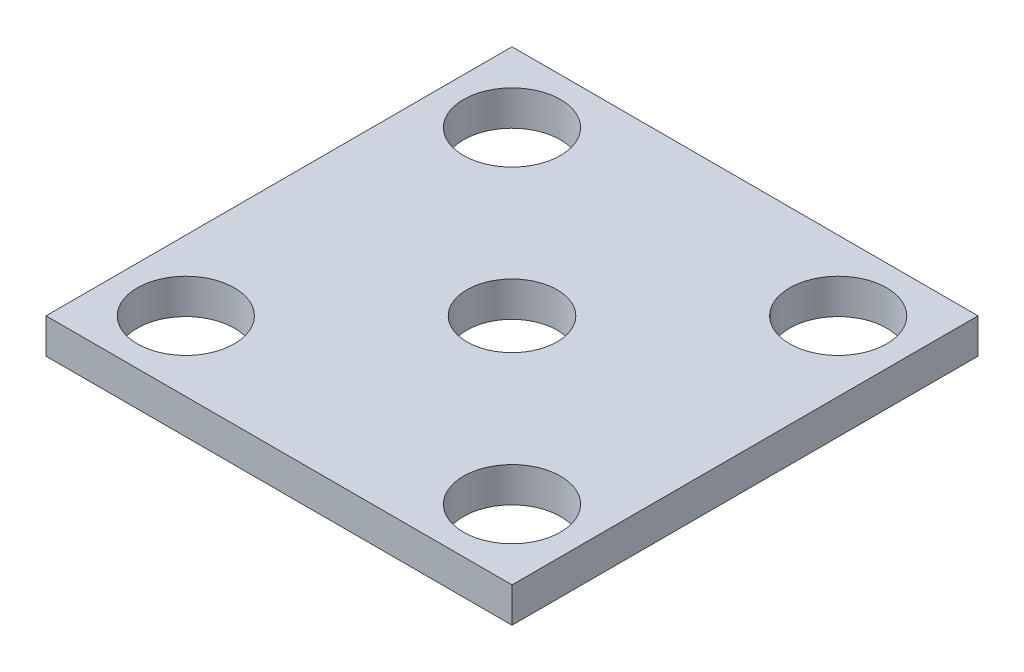
SolidWorks part; units mm, degrees
ref_plane "Front Plane" through (0, 0, 0) normal (0, 0, 1) x (1, 0, 0)
ref_plane "Top Plane" through (0, 0, 0) normal (0, 1, 0) x (1, 0, 0)
ref_plane "Right Plane" through (0, 0, 0) normal (1, 0, 0) x (0, 0, -1)
sketch "Sketch1" plane through (0, 0, 0) normal (0, 1, 0) x (1, 0, 0)
  line L1 (0, 0) -> (40, 0)
  line L2 (0, 0) -> (0, 40)
  line L3 (0, 40) -> (40, 40)
  line L4 (40, 0) -> (40, 40)
  circle A0 centre (20, 20) radius 3.875
  circle A1 centre (6, 34) radius 4.1656
  circle A2 centre (6, 6) radius 4.1656
  circle A3 centre (34, 6) radius 4.1656
  circle A4 centre (34, 34) radius 4.1656
  dimension "D3" = 6
  dimension "D5" = 6
  dimension "D7" = 6
  dimension "D9" = 6
  dimension "D1" = 40
  dimension "D2" = 40
  dimension "D4" = 6
  dimension "D6" = 6
  dimension "D8" = 6
  dimension "D10" = 6
extrude "Boss-Extrude1" add sketch "Sketch1" along normal blind 3
